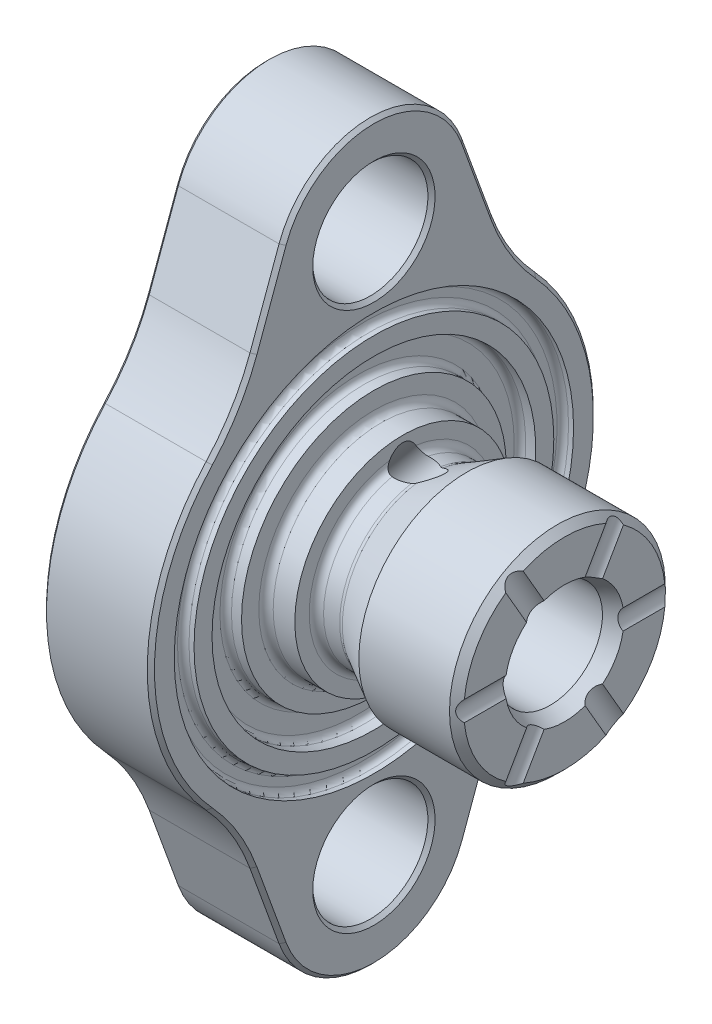
SolidWorks part; units mm, degrees
material "17CrNiMo6"
ref_plane "Front Plane" through (0, 0, 0) normal (0, 0, 1) x (1, 0, 0)
ref_plane "Top Plane" through (0, 0, 0) normal (0, 1, 0) x (1, 0, 0)
ref_plane "Right Plane" through (0, 0, 0) normal (1, 0, 0) x (0, 0, -1)
sketch "Sketch1" plane through (0, 0, 0) normal (0, 0, 1) x (1, 0, 0)
  line L0 (0, 0) -> (0, 52.5)
  line L1 (0, 52.5) -> (15, 52.5)
  line L2 (15, 52.5) -> (15, 27.75)
  line L3 (15, 27.75) -> (14.3, 27.75)
  line L4 (13.5, 26.95) -> (13.5, 25.8)
  line L5 (14.3, 25) -> (15, 25)
  line L6 (15, 25) -> (15, 22.5)
  line L7 (15, 22.5) -> (13.6, 22.5)
  line L8 (12.8, 21.7) -> (12.8, 19.2)
  line L9 (13.6, 18.4) -> (15, 18.4)
  line L10 (15, 18.4) -> (15, 15.9975)
  line L11 (16, 14.9975) -> (19, 14.9975)
  line L12 (19, 14.9975) -> (19, 13)
  line L13 (20, 12) -> (22.2411, 12)
  line L14 (22.7264, 12.1257) -> (27.9, 14.9975)
  line L15 (27.9, 14.9975) -> (41.5, 14.9975)
  line L16 (41.5, 14.9975) -> (41.5, 8.25)
  line L17 (41.5, 8.25) -> (39.5, 7.265)
  line L18 (39.5, 7.265) -> (30, 7.265)
  line L19 (30, 7.265) -> (30, 7.5)
  line L20 (30, 7.5) -> (28.5, 7.5)
  line L21 (28.5, 7.5) -> (27.9082, 6.515)
  line L22 (27.9082, 6.515) -> (19, 6.515)
  line L23 (19, 6.515) -> (19, 6.9)
  line L24 (12.5, 6.9) -> (8.5163, 0)
  line L25 (0, 0) -> (64.1591, 0) construction
  line L26 (19, 6.9) -> (12.5, 6.9)
  line L27 (0, 0) -> (8.5163, 0)
  arc A0 (14.3, 27.75) -> (13.5, 26.95) centre (14.3, 26.95) ccw
  arc A1 (14.3, 25) -> (13.5, 25.8) centre (14.3, 25.8) cw
  arc A2 (13.6, 22.5) -> (12.8, 21.7) centre (13.6, 21.7) ccw
  arc A3 (13.6, 18.4) -> (12.8, 19.2) centre (13.6, 19.2) cw
  arc A4 (20, 12) -> (19, 13) centre (20, 13) cw
  arc A5 (22.7264, 12.1257) -> (22.2411, 12) centre (22.2411, 13) cw
  arc A6 (16, 14.9975) -> (15, 15.9975) centre (16, 15.9975) cw
  point P25 (21, 12)
  point P42 (22.5, 12)
  dimension "D29" = 0.8
  dimension "D30" = 1
  dimension "D31" = 1
  dimension "D1" = 60
  dimension "D2" = 15
  dimension "D3" = 105
  dimension "D4" = 11.5
  dimension "D5" = 14.53
  dimension "D6" = 13.8
  dimension "D7" = 15
  dimension "D8" = 29.995
  dimension "D9" = 24
  dimension "D10" = 26.5
  dimension "D11" = 13
  dimension "D12" = 59
  dimension "D13" = 2
  dimension "D14" = 16.5
  dimension "D15" = 13.03
  dimension "D16" = 29
  dimension "D17" = 22.5
  dimension "D18" = 13.6
  dimension "D19" = 19
  dimension "D20" = 36.8
  dimension "D21" = 45
  dimension "D22" = 50
  dimension "D23" = 55.5
  dimension "D24" = 1.5
  dimension "D25" = 2.2
  dimension "D26" = 2
  dimension "D27" = 41.5
  dimension "D28" = 22.5
  dimension "D32" = 32.9837
revolve "Revolve1" add sketch "Sketch1" angle 360 about L25
sketch "Sketch2" plane through (0, 0, 0) normal (-1, 0, 0) x (0, 0, 1)
  line L0 (0, 0) -> (70.5057, 0) construction
  line L1 (0, 0) -> (0, 55.746) construction
  line L2 (12.6859, 42.1173) -> (16.7286, 31.0098)
  line L3 (-12.6859, 42.1173) -> (-16.7286, 31.0098)
  line L4 (12.6859, -42.1173) -> (16.7286, -31.0098)
  line L5 (-12.6859, -42.1173) -> (-16.7286, -31.0098)
  arc A0 (12.6859, 42.1173) -> (-12.6859, 42.1173) centre (0, 37.5) ccw
  arc A1 (22.8279, -20.9735) -> (22.8279, 20.9735) centre (0, 0) ccw
  arc A2 (22.8279, 20.9735) -> (16.7286, 31.0098) centre (44.9194, 41.2704) cw
  arc A3 (-22.8279, 20.9735) -> (-16.7286, 31.0098) centre (-44.9194, 41.2704) ccw
  arc A4 (-22.8279, -20.9735) -> (-22.8279, 20.9735) centre (0, 0) cw
  arc A5 (22.8279, -20.9735) -> (16.7286, -31.0098) centre (44.9194, -41.2704) ccw
  arc A6 (12.6859, -42.1173) -> (-12.6859, -42.1173) centre (0, -37.5) cw
  arc A7 (-22.8279, -20.9735) -> (-16.7286, -31.0098) centre (-44.9194, -41.2704) cw
  circle A8 centre (0, 37.5) radius 8 construction
  circle A9 centre (0, -37.5) radius 8 construction
  dimension "D1" = 27
  dimension "D2" = 62
  dimension "D3" = 75
  dimension "D5" = 30
  dimension "D6" = 102
  dimension "D7" = 16
  dimension "D4" = 20
extrude "Cut-Extrude1" cut sketch "Sketch2" against normal through all flip side to cut
sketch "Sketch3" plane through (0, 0, 0) normal (-1, 0, 0) x (0, 0, 1)
  circle A0 centre (0, 37.5) radius 8
  dimension "D1" = 16
extrude "Cut-Extrude2" cut sketch "Sketch3" against normal through all
mirror "Mirror1" about plane through (0, 0, 0) normal (0, 1, 0) of "Cut-Extrude2"
hole_wizard "CENTRE Hole1" positions "Sketch7" profile "Sketch6" legacy
sketch "Sketch7" plane through (0, 0, 0) normal (-1, 0, 0) x (0, 0, 1)
  point P0 (0, 0)
sketch "Sketch6" plane through (0, 0, 0) normal (0, 1, 0) x (0, 0, 1)
  line L0 (0, 0) -> (0, 6.2017)
  line L1 (0, 6.2017) -> (2, 5)
  line L2 (2, 5) -> (2, 1.7321)
  line L3 (2, 1.7321) -> (3, 0)
  line L4 (3, 0) -> (0, 0)
  line L5 (0, -14.3089) -> (0, 102.4216) construction
  line L6 (0, 6.2017) -> (-2, 5) construction
  line L7 (-2, 1.7321) -> (-3, 0) construction
  dimension "Diameter" = 4
  dimension "Depth" = 5
  dimension "C-Sink Diameter" = 6
  dimension "C-Sink Angle" = 60
  dimension "Drill Angle" = 118
chamfer "Chamfer2" distance 1 angle 45 1 edges at (41.5, 0, 14.9975)
sketch "Sketch8" plane through (0, 0, 0) normal (0, 0, 1) x (1, 0, 0)
  line L0 (0, 0) -> (52.9452, 0) construction
  line L2 (45.4183, -1.4) -> (41.5, -1.4)
  line L3 (45.4183, -1.4) -> (45.4183, 1.4)
  line L4 (45.4183, 1.4) -> (41.5, 1.4)
  line L5 (40.9283, -1.4) -> (40.9283, 1.4) construction
  line L6 (41.5, 1.4) -> (41.5, -1.4) construction
  line L7 (41.5, -13.9975) -> (41.5, 13.9975) construction
  arc A0 (41.5, 1.4) -> (41.5, -1.4) centre (42.9283, 0) ccw
  dimension "D2" = 2
  dimension "D1" = 2.8
extrude "Cut-Extrude4" cut sketch "Sketch8" against normal through all
ref_axis "Axis1" through (30, 0, 0) along (1, 0, 0)
pattern_circular "CirPattern1" count 6 over 360 about axis through (30, 0, 0) along (1, 0, 0) of "Cut-Extrude4"
ref_plane "Plane1" through (0, 0, 0) normal (0.6428, 0.766, 0) x (0, 0, -1)
ref_plane "Plane2" through (14.5855, 17.3824, 0) normal (0.6428, 0.766, 0) x (0, 0, -1)
sketch "Sketch14" plane through (0, 0, 0) normal (0, 0, 1) x (1, 0, 0)
  line L0 (20.5, 12) -> (10.4308, 0) construction
  line L1 (0, 0) -> (45.7767, 0) construction
  line L2 (41.5, 12.7614) -> (41.5, 7.7411) construction
  line L4 (0, 0) -> (64.1591, 0) construction
  line L5 (20, 12) -> (22.2411, 12) construction
  line L6 (25.8044, 14.4322) -> (15.5826, 2.2504)
  line L7 (25.8044, 14.4322) -> (23.8893, 16.0392)
  line L8 (15.5826, 2.2504) -> (12.3191, 2.2504)
  line L9 (23.8893, 16.0392) -> (12.3191, 2.2504)
  dimension "D1" = 50
  dimension "D2" = 21
  dimension "D3" = 5
  dimension "D4" = 5.2728
  dimension "D5" = 18
revolve "Cut-Revolve1" cut sketch "Sketch14" angle 360 about L9
pattern_circular "CirPattern2" count 2 over 360 about axis through (30, 0, 0) along (1, 0, 0) of "Cut-Revolve1"
sketch "Sketch13" plane through (0, 0, 0) normal (-1, 0, 0) x (0, 0, 1)
  line L0 (8, 16.3705) -> (8, -17.6011) construction
  line L1 (12.8425, 6.2687) -> (12.8425, -4.52) construction
  text T0 "7372 2965 01 - B\r\n11111 - XX" font "Century Gothic" height 3
  line B0 (12.8425, -2.4498) -> (12.8425, 1.4724)
  line B1 (13.642, -1.8688) -> (13.642, 1.0177)
  line B2 (12.9625, 1.4041) -> (13.522, 1.086)
  line B3 (16.9756, -0.0372) -> (16.9756, 0.6468)
  line B4 (19.6923, 1.4724) -> (16.9756, -0.0372)
  line B5 (13.642, -1.8688) -> (16.2187, -0.4475)
  line B6 (16.2187, -3.6028) -> (15.5991, -3.9613)
  line B7 (19.6923, -0.4525) -> (19.6923, 1.4724)
  line B8 (16.9756, -3.19) -> (16.2187, -3.6028)
  line B9 (16.9756, -3.19) -> (18.7235, -2.1534)
  line B10 (12.8425, 1.4724) -> (12.8425, 4.4693)
  line B11 (15.8055, 2.7844) -> (12.8425, 4.4693)
  line B12 (16.3391, -3.4279) -> (16.8556, -3.1217)
  line B13 (19.5723, -0.4525) -> (19.5723, 1.2684)
  line B14 (19.5723, 1.2684) -> (16.9756, -0.1745)
  line B15 (16.8556, 0.6468) -> (16.8556, -3.1217)
  line B16 (15.7434, 2.6817) -> (12.9625, 4.263)
  line B17 (12.9625, 1.5422) -> (12.9625, 4.263)
  line B18 (16.3391, -0.3779) -> (16.3391, -3.4279)
  line B19 (12.9625, 1.5422) -> (16.3391, -0.3779)
  line B20 (16.2187, -3.4641) -> (15.5367, -3.8587)
  line B21 (12.9625, -2.4498) -> (12.9625, 1.4041)
  line B22 (16.9756, -0.1745) -> (16.9756, -3.0505)
  line B23 (16.9756, -3.0505) -> (18.6622, -2.0502)
  line B24 (13.522, -2.0721) -> (13.522, 1.086)
  line B25 (13.522, -2.0721) -> (16.2187, -0.5845)
  line B26 (16.2187, -0.5845) -> (16.2187, -3.4641)
  line B27 (13.642, 1.0177) -> (16.2187, -0.4475)
  arc B28 (18.7235, -2.1534) -> (19.6923, -0.4525) centre (17.7147, -0.4525) ccw
  arc B29 (12.8425, -2.4498) -> (15.5991, -3.9613) centre (14.6352, -2.4498) ccw
  arc B30 (16.9756, 0.6468) -> (15.8055, 2.7844) centre (14.4379, 0.6468) ccw
  arc B31 (18.6622, -2.0502) -> (19.5723, -0.4525) centre (17.7147, -0.4525) ccw
  arc B32 (16.8556, 0.6468) -> (15.7434, 2.6817) centre (14.4379, 0.6468) ccw
  arc B33 (12.9625, -2.4498) -> (15.5367, -3.8587) centre (14.6352, -2.4498) ccw
  dimension "D1" = 8
sketch_block_instance "SKETCH LOGO-1"
sketch_block "SKETCH LOGO" parameters "D1"=29.059, "D2"=11.4163, "D3"=29.624, "D4"=6.8884
extrude "Extrude1" cut sketch "Sketch13" against normal blind 0.1
chamfer "Chamfer3" distance 0.5 angle 45 28 edges at (0, -25.6903, 19.2824) (0, 0, 31) (0, -36.5635, 14.7072) (0, 25.6903, 19.2824) (0, -51, 0) (0, 36.5635, 14.7072) (0, -36.5635, -14.7072) (0, 51, 0) (0, -25.6903, -19.2824) (0, 36.5635, -14.7072) (0, 0, -31) (0, 25.6903, -19.2824) (0, 37.5, 8) (0, -37.5, 8) (15, -25.6903, 19.2824) (15, 0, 31) (15, -36.5635, 14.7072) (15, 25.6903, 19.2824) (15, -51, 0) (15, 36.5635, 14.7072) (15, -36.5635, -14.7072) (15, 51, 0) (15, -25.6903, -19.2824) (15, 36.5635, -14.7072) (15, 0, -31) (15, 25.6903, -19.2824) (15, -37.5, 8) (15, 37.5, 8)
